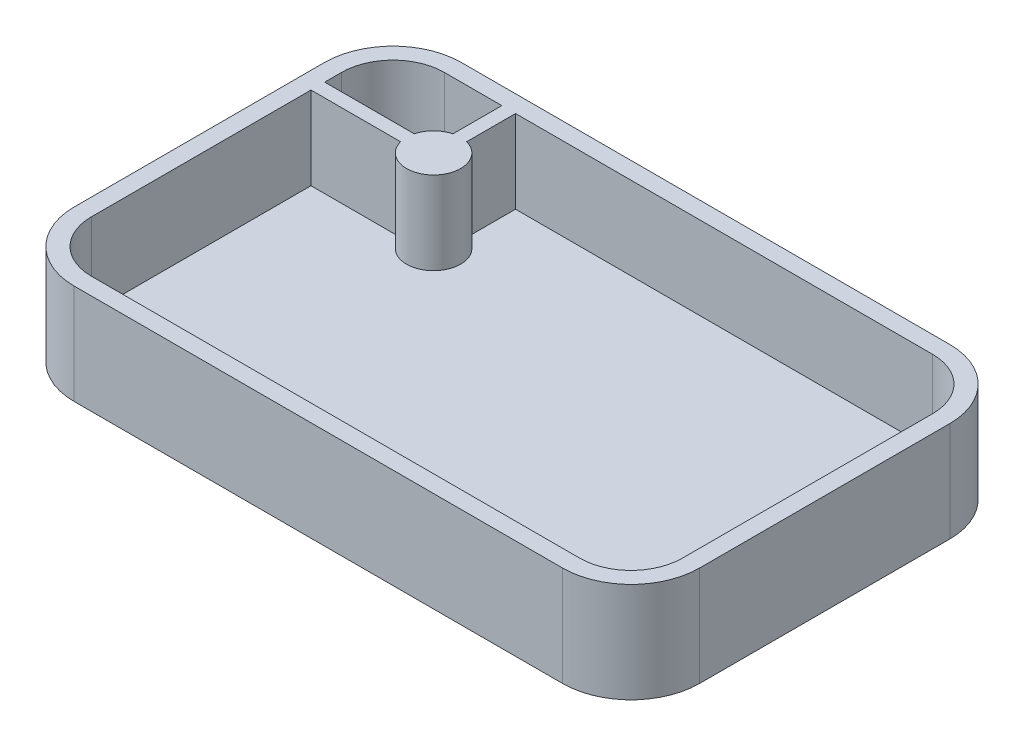
SolidWorks part; units mm, degrees
ref_plane "Front Plane" through (0, 0, 0) normal (0, 0, 1) x (1, 0, 0)
ref_plane "Top Plane" through (0, 0, 0) normal (0, 1, 0) x (1, 0, 0)
ref_plane "Right Plane" through (0, 0, 0) normal (1, 0, 0) x (0, 0, -1)
sketch "Sketch1" plane through (0, 0, 0) normal (0, 1, 0) x (1, 0, 0)
  line L1 (12.7, 0) -> (103.2541, 0)
  line L2 (0, 12.7) -> (0, 59.099)
  line L3 (12.7, 71.799) -> (103.2541, 71.799)
  line L4 (115.9541, 12.7) -> (115.9541, 59.099)
  arc A0 (103.2541, 0) -> (115.9541, 12.7) centre (103.2541, 12.7) ccw
  arc A1 (103.2541, 71.799) -> (115.9541, 59.099) centre (103.2541, 59.099) cw
  arc A2 (0, 59.099) -> (12.7, 71.799) centre (12.7, 59.099) cw
  arc A3 (12.7, 0) -> (0, 12.7) centre (12.7, 12.7) cw
  point P13 (0, 0)
  dimension "D1" = 12.7
extrude "Boss-Extrude1" add sketch "Sketch1" against normal blind 18.542
shell "Shell1" thickness 3.175
sketch "Sketch2" plane through (0, 0, 0) normal (0, 1, 0) x (1, 0, 0)
  circle A0 centre (24.6378, 54.7015) radius 5.0193
extrude "Boss-Extrude2" add sketch "Sketch2" against normal up to next
sketch "Sketch3" plane through (0, 0, 0) normal (0, 1, 0) x (1, 0, 0)
  line L0 (19.6185, 54.7015) -> (3.175, 54.7015)
  line L1 (3.175, 59.099) -> (3.175, 12.7) construction
  line L2 (24.6378, 59.7208) -> (24.6378, 68.624)
  line L3 (103.2541, 68.624) -> (12.7, 68.624) construction
  circle A0 centre (24.6378, 54.7015) radius 5.0193 construction
  circle A1 centre (24.6378, 54.7015) radius 5.0193 construction
rib "Rib1" sketch "Sketch3" sketch "Sketch3" thickness 2.54 extrusion direction normal to sketch draft on no parameters "D1"=2.54
